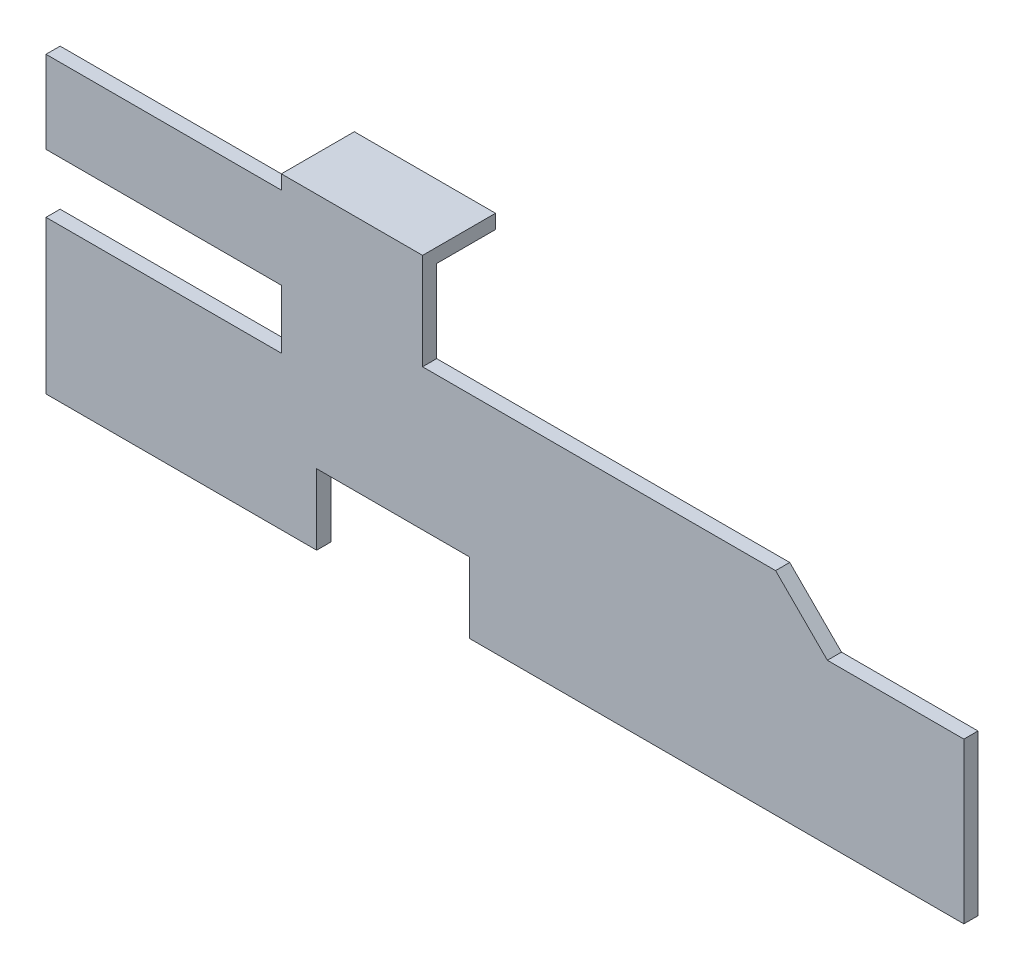
SolidWorks part; units mm, degrees
material "铜"
ref_plane "前视基准面" through (0, 0, 0) normal (0, 0, 1) x (1, 0, 0)
ref_plane "上视基准面" through (0, 0, 0) normal (0, 1, 0) x (1, 0, 0)
ref_plane "右视基准面" through (0, 0, 0) normal (1, 0, 0) x (0, 0, -1)
sketch "草图1" plane through (0, 0, 0) normal (0, 0, 1) x (1, 0, 0)
  line L0 (0, 0) -> (11.5, 0)
  line L1 (11.5, 0) -> (11.5, 3)
  line L2 (11.5, 3) -> (18, 3)
  line L3 (18, 3) -> (18, 0)
  line L4 (18, 0) -> (39, 0)
  line L5 (39, 0) -> (39, 6.8)
  line L6 (39, 6.8) -> (33.2, 6.8)
  line L7 (33.2, 6.8) -> (31, 9)
  line L8 (31, 9) -> (16, 9)
  line L9 (16, 9) -> (16, 15)
  line L10 (16, 15) -> (10, 15)
  line L11 (10, 15) -> (10, 12.5)
  line L12 (10, 12.5) -> (0, 12.5)
  line L13 (0, 12.5) -> (0, 9)
  line L14 (0, 9) -> (10, 9)
  line L15 (10, 9) -> (10, 6.5)
  line L16 (10, 6.5) -> (0, 6.5)
  line L17 (0, 6.5) -> (0, 0)
  dimension "D1" = 39
  dimension "D2" = 15
  dimension "D3" = 16
  dimension "D4" = 9
  dimension "D5" = 15
  dimension "D6" = 6.8
  dimension "D7" = 6.5
  dimension "D8" = 11.5
  dimension "D9" = 10
  dimension "D10" = 2.5
  dimension "D11" = 6.5
  dimension "D12" = 3.5
  dimension "D13" = 3
  dimension "D14" = 10
  dimension "D15" = 2.2
extrude "凸台-拉伸1" add sketch "草图1" along normal blind 0.6
sketch "草图2" plane through (0, 0, 0) normal (0, 0, -1) x (-1, 0, 0)
  line L0 (-16, 9) -> (-16, 15) construction
  line L1 (-10, 12.5) -> (-16, 12.5)
  line L2 (-10, 12.5) -> (-10, 13.1)
  line L3 (-10, 13.1) -> (-16, 13.1)
  line L4 (-16, 12.5) -> (-16, 13.1)
  dimension "D1" = 0.6
extrude "凸台-拉伸2" add sketch "草图2" along normal blind 2.5
sketch "草图3" plane through (0, 0, 0) normal (0, 0, -1) x (-1, 0, 0)
  line L1 (-16, 15) -> (-10, 15)
  line L2 (-16, 15) -> (-16, 13.1)
  line L3 (-16, 13.1) -> (-10, 13.1)
  line L4 (-10, 15) -> (-10, 13.1)
extrude "切除-拉伸1" cut sketch "草图3" against normal through all
